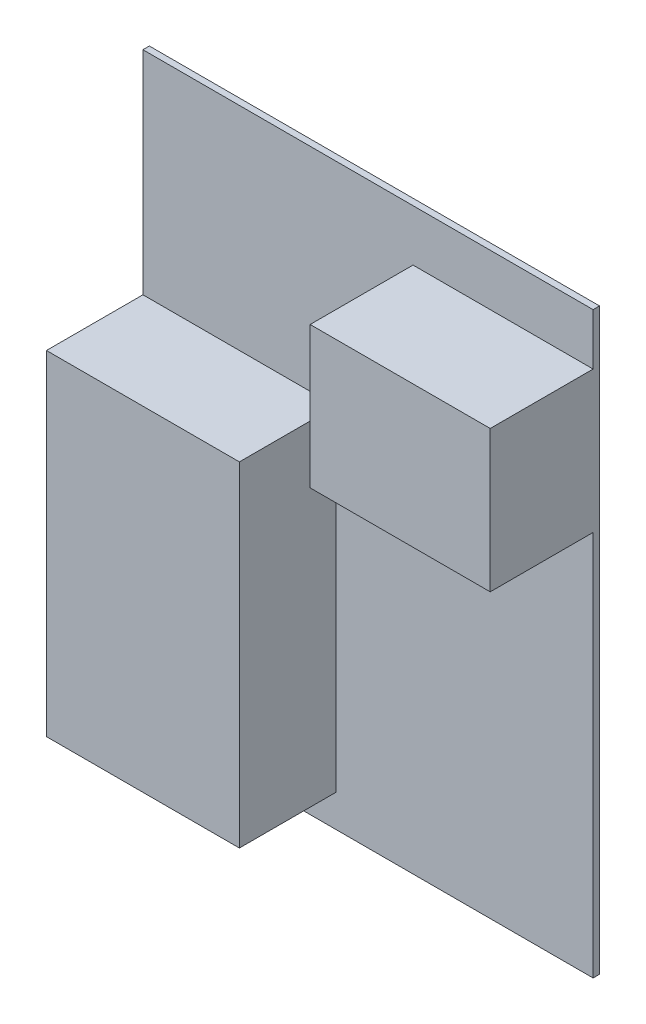
SolidWorks part; units mm, degrees
ref_plane "Front Plane" through (0, 0, 0) normal (0, 0, 1) x (1, 0, 0)
ref_plane "Top Plane" through (0, 0, 0) normal (0, 1, 0) x (1, 0, 0)
ref_plane "Right Plane" through (0, 0, 0) normal (1, 0, 0) x (0, 0, -1)
sketch "Sketch2" plane through (0, 0, 0) normal (0, 0, 1) x (1, 0, 0)
  line L1 (-35, -45) -> (35, -45)
  line L2 (-35, -45) -> (-35, 45)
  line L3 (-35, 45) -> (35, 45)
  line L4 (35, -45) -> (35, 45)
  line L5 (-35, -45) -> (35, 45) construction
  line L6 (-35, 45) -> (35, -45) construction
  point P0 (0, 0)
  dimension "D1" = 70
  dimension "D2" = 90
extrude "Boss-Extrude1" add sketch "Sketch2" along normal blind 1
sketch "Sketch3" plane through (0, 0, 1) normal (0, 0, 1) x (1, 0, 0)
  line L0 (35, -45) -> (35, 45) construction
  line L1 (35, 37) -> (7, 37)
  line L2 (35, 37) -> (35, 15)
  line L3 (35, 15) -> (7, 15)
  line L4 (7, 37) -> (7, 15)
  line L5 (35, 45) -> (-35, 45) construction
  dimension "D1" = 8
  dimension "D2" = 22
  dimension "D3" = 28
extrude "Boss-Extrude2" add sketch "Sketch3" along normal blind 16
sketch "Sketch4" plane through (0, 0, 1) normal (0, 0, 1) x (1, 0, 0)
  line L0 (-35, 45) -> (-35, -45) construction
  line L1 (-35, -40) -> (-5, -40)
  line L2 (-35, -40) -> (-35, 12)
  line L3 (-35, 12) -> (-5, 12)
  line L4 (-5, -40) -> (-5, 12)
  line L5 (-35, -45) -> (35, -45) construction
  dimension "D1" = 5
  dimension "D2" = 30
  dimension "D3" = 52
extrude "Boss-Extrude3" add sketch "Sketch4" along normal blind 15
